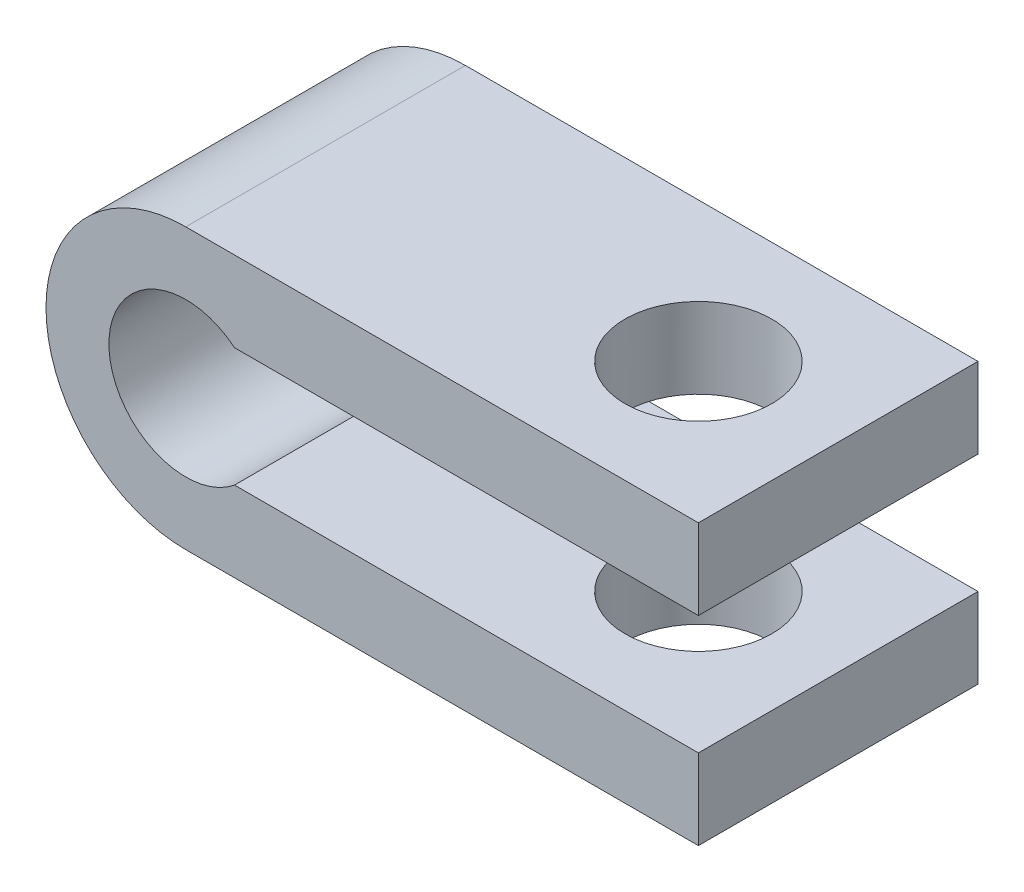
SolidWorks part; units mm, degrees
ref_plane "Front Plane" through (0, 0, 0) normal (0, 0, 1) x (1, 0, 0)
ref_plane "Top Plane" through (0, 0, 0) normal (0, 1, 0) x (1, 0, 0)
ref_plane "Right Plane" through (0, 0, 0) normal (1, 0, 0) x (0, 0, -1)
sketch "Sketch1" plane through (0, 0, 0) normal (0, 0, 1) x (1, 0, 0)
  line L0 (0, 6) -> (22, 6)
  line L1 (22, 6) -> (22, 2.5527)
  line L2 (22, 2.5527) -> (2.0913, 2.5527)
  line L3 (-11.5353, 0) -> (18.1518, 0) construction
  line L4 (22, -2.5527) -> (2.0913, -2.5527)
  line L5 (22, -6) -> (22, -2.5527)
  line L6 (0, -6) -> (22, -6)
  arc A0 (2.0913, 2.5527) -> (2.0913, -2.5527) centre (0, 0) ccw
  arc A2 (0, 6) -> (0, -6) centre (0, 0) ccw
  dimension "D1" = 3.3
  dimension "D2" = 6
  dimension "D3" = 22
  dimension "D4" = 5.1054
extrude "Boss-Extrude1" add sketch "Sketch1" along normal blind 12
sketch "Sketch2" plane through (0, 0, 0) normal (0, 1, 0) x (1, 0, 0)
  circle A0 centre (16, -6) radius 3.15
  dimension "D3" = 6.3
  dimension "D1" = 16
  dimension "D2" = 6
extrude "Cut-Extrude1" cut sketch "Sketch2" against normal through all and the other way through all
